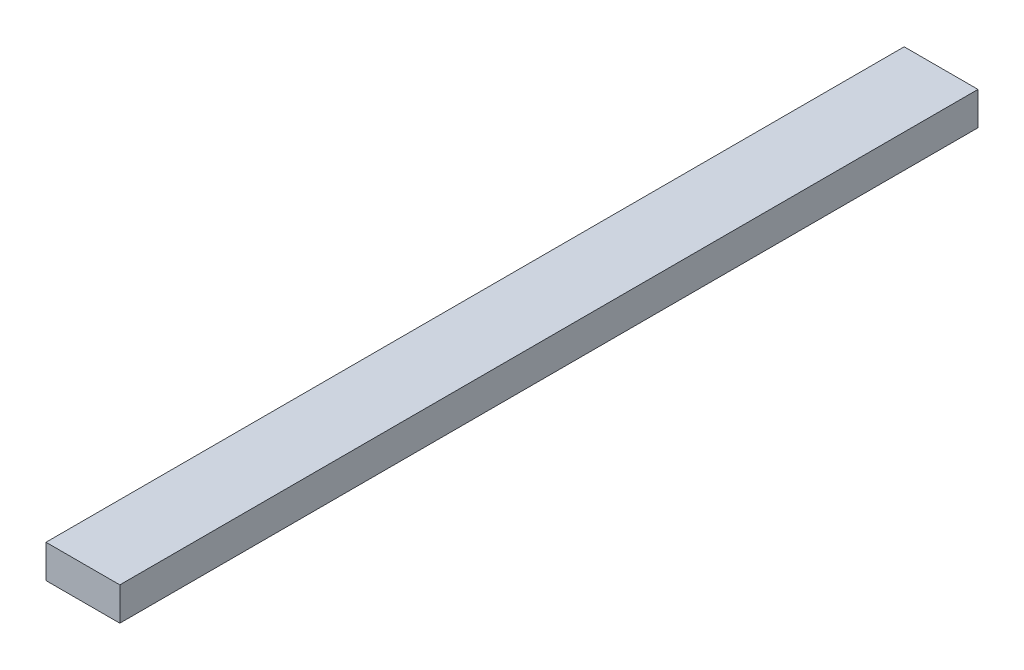
SolidWorks part; units mm, degrees
ref_plane "Front Plane" through (0, 0, 0) normal (0, 0, 1) x (1, 0, 0)
ref_plane "Top Plane" through (0, 0, 0) normal (0, 1, 0) x (1, 0, 0)
ref_plane "Right Plane" through (0, 0, 0) normal (1, 0, 0) x (0, 0, -1)
sketch "Sketch1" plane through (0, 0, 0) normal (0, 0, 1) x (1, 0, 0)
  line L1 (-20, -9) -> (20, -9)
  line L2 (-20, -9) -> (-20, 9)
  line L3 (-20, 9) -> (20, 9)
  line L4 (20, -9) -> (20, 9)
  line L5 (0, 9) -> (0, -9) construction
  line L6 (-20, 0) -> (20, 0) construction
  point P0 (0, 0)
  dimension "D1" = 18
  dimension "D2" = 40
extrude "Boss-Extrude1" add sketch "Sketch1" along normal blind 465
